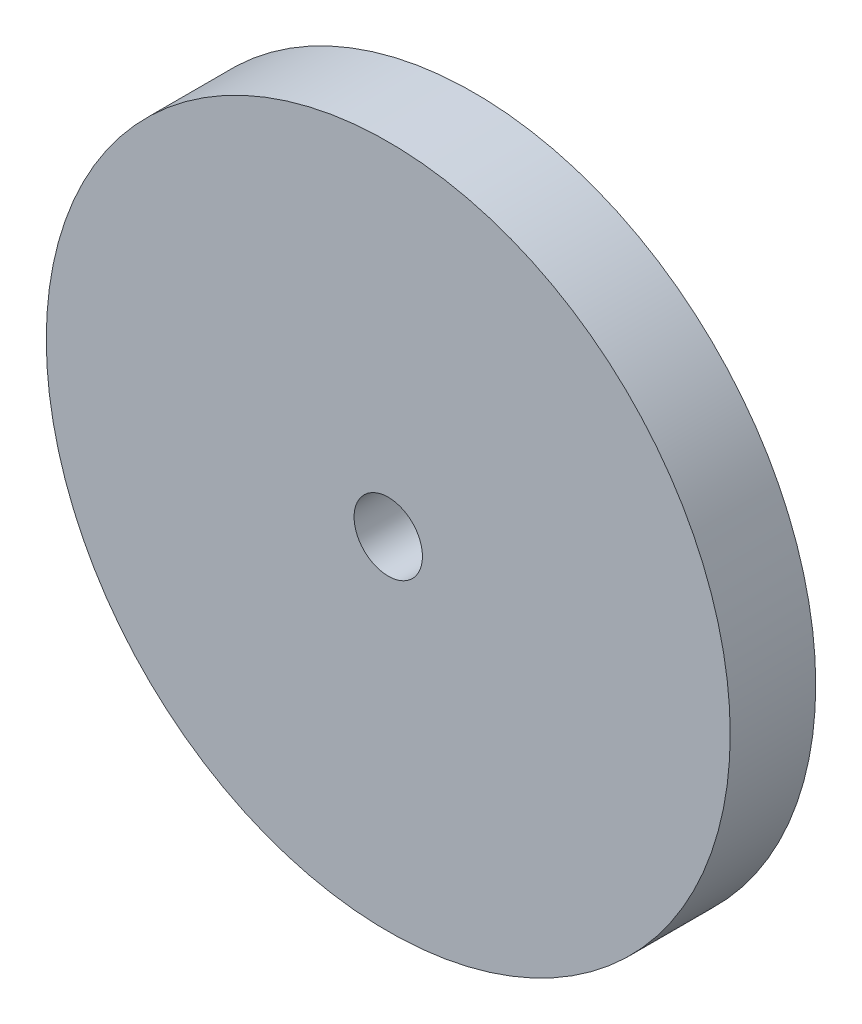
SolidWorks part; units mm, degrees
ref_plane "Front Plane" through (0, 0, 0) normal (0, 0, 1) x (1, 0, 0)
ref_plane "Top Plane" through (0, 0, 0) normal (0, 1, 0) x (1, 0, 0)
ref_plane "Right Plane" through (0, 0, 0) normal (1, 0, 0) x (0, 0, -1)
sketch "Sketch1" plane through (0, 0, 0) normal (0, 0, 1) x (1, 0, 0)
  circle A0 centre (0, 0) radius 20
  dimension "D1" = 40
extrude "Boss-Extrude1" add sketch "Sketch1" along normal mid plane 5 contours A0
sketch "Sketch2" plane through (0, 0, 2.5) normal (0, 0, 1) x (1, 0, 0)
  circle A0 centre (0, 0) radius 2
  dimension "D1" = 4
extrude "Cut-Extrude1" cut sketch "Sketch2" against normal up to surface (5 mm away) up to face at (20, 0, -2.5)
